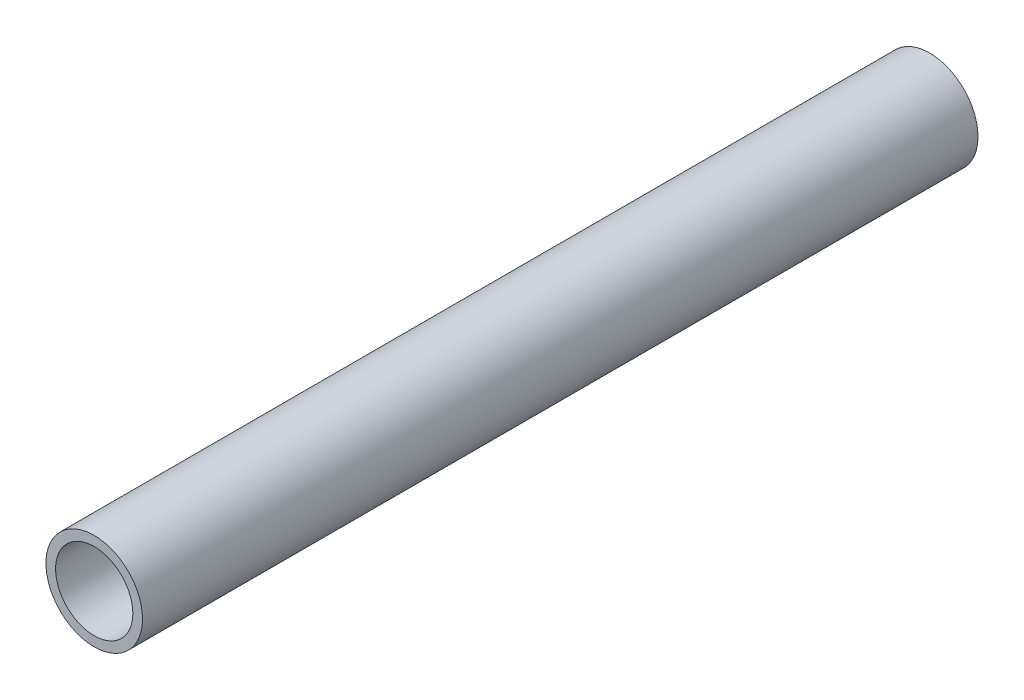
SolidWorks part; units mm, degrees
material "Thornel Mat VMA"
ref_plane "前视基准面" through (0, 0, 0) normal (0, 0, 1) x (1, 0, 0)
ref_plane "上视基准面" through (0, 0, 0) normal (0, 1, 0) x (1, 0, 0)
ref_plane "右视基准面" through (0, 0, 0) normal (1, 0, 0) x (0, 0, -1)
other "Configuration Table"
sketch "草图1" plane through (0, 0, 0) normal (0, 0, 1) x (1, 0, 0)
  circle A0 centre (0, 0) radius 10
  circle A1 centre (0, 0) radius 8
  dimension "D1" = 20
  dimension "D2" = 16
extrude "凸台-拉伸1" add sketch "草图1" along normal blind 173
